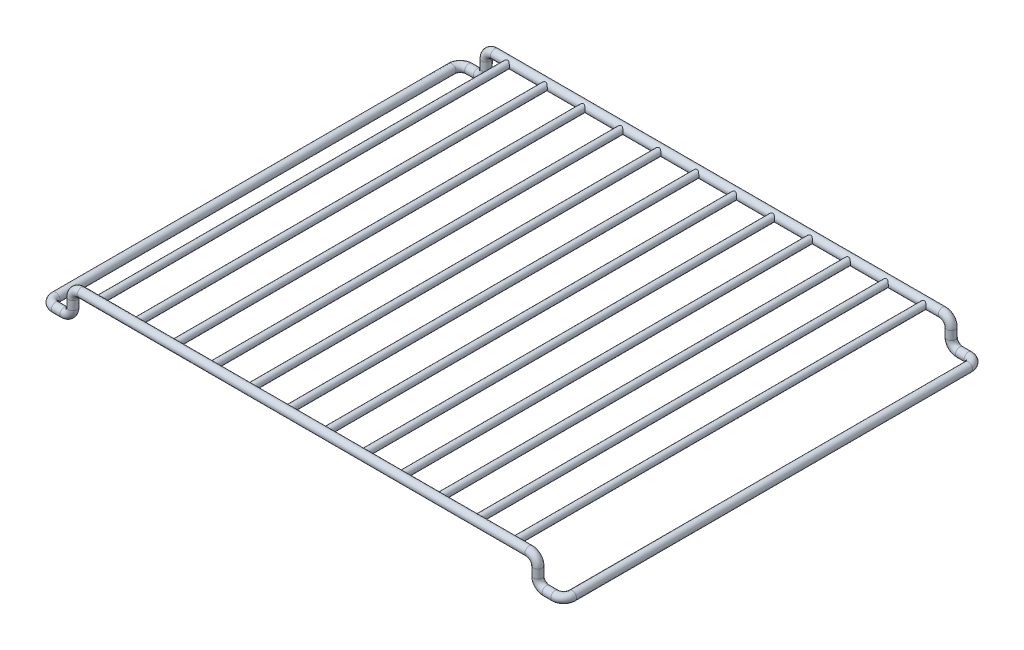
SolidWorks part; units mm, degrees
ref_plane "Front" through (0, 0, 0) normal (0, 0, 1) x (1, 0, 0)
ref_plane "Top" through (0, 0, 0) normal (0, 1, 0) x (1, 0, 0)
ref_plane "Right" through (0, 0, 0) normal (1, 0, 0) x (0, 0, -1)
sketch3d "3DSketch1"
  line L0 (0, 0, 0) -> (130, 0, 0)
  line L1 (135, -5, 0) -> (135, -10, 0)
  line L2 (140, -15, 0) -> (145, -15, 0)
  line L3 (150, -15, -5) -> (150, -15, -235)
  line L4 (145, -15, -240) -> (140, -15, -240)
  line L5 (135, -10, -240) -> (135, -5, -240)
  line L6 (130, 0, -240) -> (0, 0, -240)
  arc A0 (145, -15, 0) -> (150, -15, -5) centre (145, -15, -5) ccw
  arc A1 (135, -10, 0) -> (140, -15, 0) centre (140, -10, 0) ccw
  arc A2 (130, 0, 0) -> (135, -5, 0) centre (130, -5, 0) ccw
  arc A3 (150, -15, -235) -> (145, -15, -240) centre (145, -15, -235) ccw
  arc A4 (140, -15, -240) -> (135, -10, -240) centre (140, -10, -240) ccw
  arc A5 (135, -5, -240) -> (130, 0, -240) centre (130, -5, -240) ccw
  point P11 (150, -15, 0)
  point P12 (145, -10, -5)
  point P15 (135, -15, 0)
  point P16 (140, -10, 5)
  point P19 (135, 0, 0)
  point P20 (130, -5, -5)
  point P23 (150, -15, -240)
  point P24 (145, -10, -235)
  point P27 (135, -15, -240)
  point P28 (140, -10, -245)
  point P31 (135, 0, -240)
  point P32 (130, -5, -235)
  dimension "D8" = 5
  dimension "D1" = 135
  dimension "D2" = 15
  dimension "D3" = 240
  dimension "D4" = 15
  dimension "D5" = 135
  dimension "D6" = 15
  dimension "D7" = 15
sketch "Sketch1" plane through (0, 0, 0) normal (1, 0, 0) x (0, 0, -1)
  circle A0 centre (0, 0) radius 2.5
  dimension "D1" = 5
sweep "Sweep1" add profiles "Sketch1" path "3DSketch1"
sketch "Sketch2" plane through (0, 0, 0) normal (0, 0, 1) x (1, 0, 0)
  circle A0 centre (11, 0) radius 2
  dimension "D1" = 4
  dimension "D2" = 11
extrude "Boss-Extrude2" add sketch "Sketch2" against normal up to surface (237.5 mm away) up to face at (0, 0, -237.5)
pattern_linear "LPattern1" count 6 spacing 22 along (1, 0, 0) of "Boss-Extrude2"
mirror "Mirror1" about plane through (0, 0, 0) normal (1, 0, 0) of bodies 104
